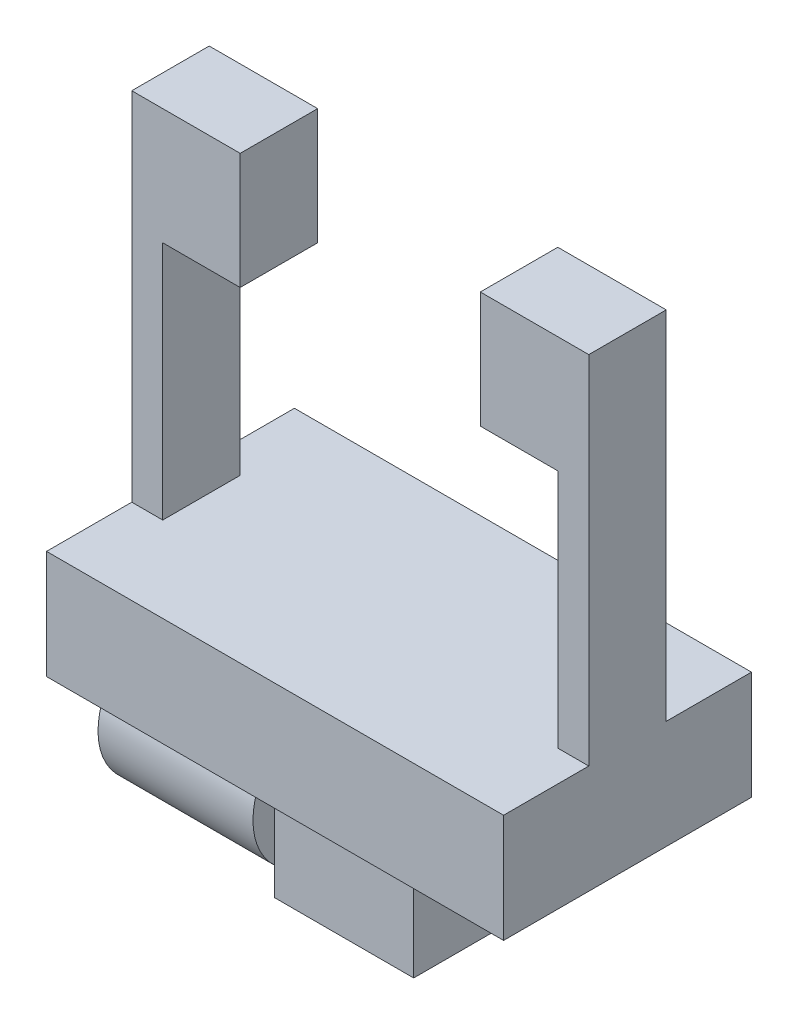
SolidWorks part; units mm, degrees
material "6061-T6 (SS)"
ref_plane "Front Plane" through (0, 0, 0) normal (0, 0, 1) x (1, 0, 0)
ref_plane "Top Plane" through (0, 0, 0) normal (0, 1, 0) x (1, 0, 0)
ref_plane "Right Plane" through (0, 0, 0) normal (1, 0, 0) x (0, 0, -1)
sketch "Sketch1" plane through (0, 0, 0) normal (0, 0, 1) x (1, 0, 0)
  line L1 (-37.465, -8.89) -> (37.465, -8.89)
  line L2 (-37.465, -8.89) -> (-37.465, 8.89)
  line L3 (-37.465, 8.89) -> (37.465, 8.89)
  line L4 (37.465, -8.89) -> (37.465, 8.89)
  line L5 (-37.465, -8.89) -> (37.465, 8.89) construction
  line L6 (-37.465, 8.89) -> (37.465, -8.89) construction
  point P0 (0, 0)
  dimension "D1" = 74.93
  dimension "D2" = 17.78
extrude "Boss-Extrude1" add sketch "Sketch1" along normal mid plane 40.64
sketch "Sketch2" plane through (0, 0, 0) normal (0, 0, 1) x (1, 0, 0)
  line L1 (-37.465, 8.89) -> (-32.385, 8.89)
  line L2 (-37.465, 8.89) -> (-37.465, 48.26)
  line L3 (-37.465, 48.26) -> (-32.385, 48.26)
  line L4 (-32.385, 8.89) -> (-32.385, 48.26)
  line L5 (37.465, 8.89) -> (32.385, 8.89)
  line L6 (37.465, 8.89) -> (37.465, 48.26)
  line L7 (37.465, 48.26) -> (32.385, 48.26)
  line L8 (32.385, 8.89) -> (32.385, 48.26)
  dimension "D1" = 5.08
  dimension "D2" = 39.37
  dimension "D3" = 5.08
  dimension "D4" = 39.37
extrude "Boss-Extrude2" add sketch "Sketch2" along normal mid plane 12.7
sketch "Sketch3" plane through (0, 0, 0) normal (0, 0, 1) x (1, 0, 0)
  line L1 (37.465, 48.26) -> (19.685, 48.26)
  line L2 (37.465, 48.26) -> (37.465, 67.31)
  line L3 (37.465, 67.31) -> (19.685, 67.31)
  line L4 (19.685, 48.26) -> (19.685, 67.31)
  line L5 (-37.465, 48.26) -> (-19.685, 48.26)
  line L6 (-37.465, 48.26) -> (-37.465, 67.31)
  line L7 (-37.465, 67.31) -> (-19.685, 67.31)
  line L8 (-19.685, 48.26) -> (-19.685, 67.31)
  dimension "D1" = 17.78
  dimension "D2" = 19.05
  dimension "D3" = 17.78
  dimension "D4" = 19.05
extrude "Boss-Extrude3" add sketch "Sketch3" along normal mid plane 12.7
sketch "Sketch5" plane through (0, 0, 0) normal (0, 0, 1) x (1, 0, 0)
  line L1 (-12.832, -8.89) -> (10.028, -8.89)
  line L2 (-12.832, -8.89) -> (-12.832, -34.29)
  line L3 (-12.832, -34.29) -> (10.028, -34.29)
  line L4 (10.028, -8.89) -> (10.028, -34.29)
  dimension "D1" = 22.86
  dimension "D2" = 25.4
extrude "Boss-Extrude4" add sketch "Sketch5" along normal mid plane 15.24
sketch "Sketch6" plane through (-12.832, 0, 0) normal (-1, 0, 0) x (0, 0, 1)
  circle A0 centre (0, -21.59) radius 11.1125
  dimension "D1" = 22.225
extrude "Boss-Extrude5" add sketch "Sketch6" along normal blind 25.4
